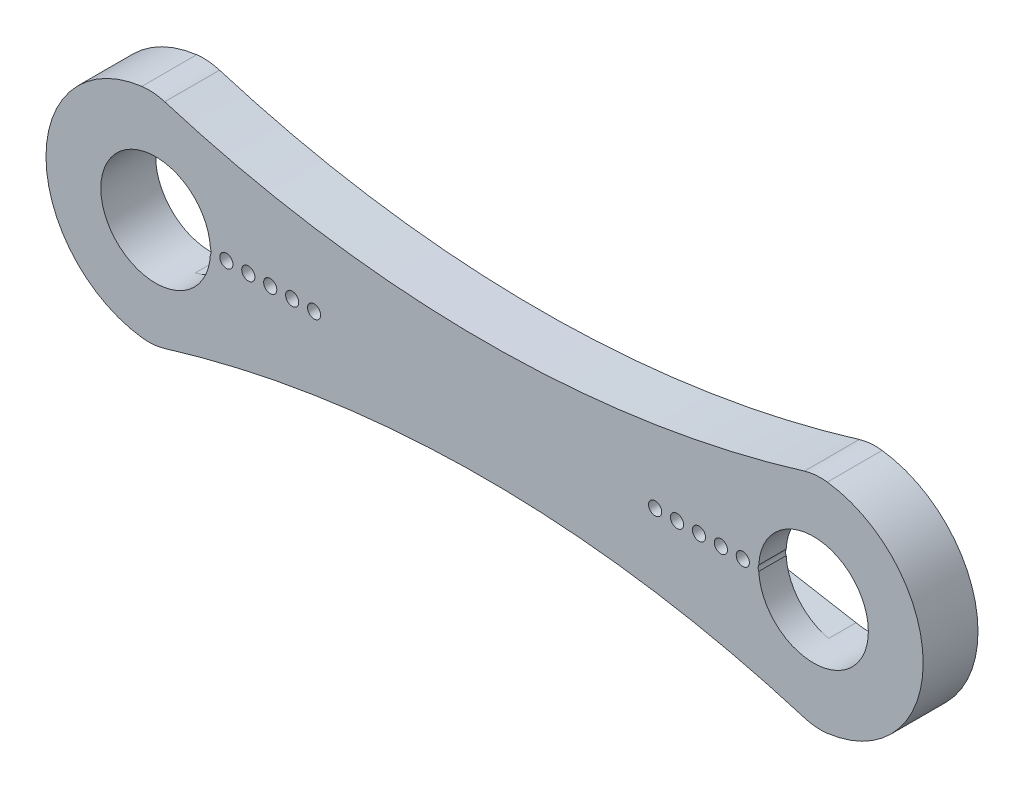
SolidWorks part; units mm, degrees
ref_plane "前视基准面" through (0, 0, 0) normal (0, 0, 1) x (1, 0, 0)
ref_plane "上视基准面" through (0, 0, 0) normal (0, 1, 0) x (1, 0, 0)
ref_plane "右视基准面" through (0, 0, 0) normal (1, 0, 0) x (0, 0, -1)
other "Configuration Table"
sketch "Sketch1" plane through (0, 0, 0) normal (0, 0, 1) x (1, 0, 0)
  line L0 (0, 0) -> (60, 0) construction
  arc A0 (0, 10) -> (0, -10) centre (0, 0) ccw
  circle A1 centre (0, 0) radius 5
  arc A3 (60, -10) -> (60, 10) centre (60, 0) ccw
  circle A4 centre (60, 0) radius 5
  arc A5 (0, 10) -> (60, 10) centre (30, 105.3939) ccw
  arc A6 (0, -10) -> (60, -10) centre (30, -105.3939) cw
  dimension "D1" = 20
  dimension "D2" = 10
  dimension "D3" = 20
  dimension "D4" = 10
  dimension "D6" = 100
  dimension "D5" = 60
extrude "Boss-Extrude1" add sketch "Sketch1" along normal blind 5
fillet "Fillet1" radius 5 4 edges at (60, 10, 2.5) (60, -10, 2.5) (0, -10, 2.5) (0, 10, 2.5)
sketch "Sketch2" plane through (0, 0, 0) normal (0, 0, -1) x (-1, 0, 0)
  line L0 (0, 0) -> (-4.45, 0) construction
  circle A0 centre (-4.45, 0) radius 0.6
  circle A1 centre (-6.45, 0) radius 0.6
  circle A2 centre (-8.45, 0) radius 0.6
  circle A3 centre (-10.45, 0) radius 0.6
  circle A4 centre (-12.45, 0) radius 0.6
  circle A5 centre (-14.45, 0) radius 0.6
  dimension "D1" = 1.2
  dimension "D2" = 4.45
  dimension "D3" = 6
extrude "Cut-Extrude1" cut sketch "Sketch2" against normal blind 5
sketch "Sketch3" plane through (0, 0, 0) normal (0, 0, -1) x (-1, 0, 0)
  line L0 (-14.8825, 2.4623) -> (-0.8651, 4.9246)
  line L1 (-14.45, 0) -> (0, 0) construction
  line L2 (-15.0123, -2.4359) -> (-1.1246, -4.8719)
  circle A0 centre (-14.45, 0) radius 2.5
  circle A1 centre (0, 0) radius 5
  arc A2 (-4.9935, -0.2541) -> (-4.9935, 0.2541) centre (0, 0) ccw construction
  dimension "D1" = 5
extrude "Cut-Extrude2" cut sketch "Sketch3" against normal blind 2.5
sketch "Sketch4" plane through (0, 0, 0) normal (0, 0, -1) x (-1, 0, 0)
  line L0 (0, 0) -> (-60, 0) construction
ref_plane "Plane1" through (30, 0, 0) normal (1, 0, 0) x (0, 0, -1)
mirror "Mirror2" about plane through (30, 0, 0) normal (1, 0, 0) of "Cut-Extrude2", "Cut-Extrude1"
